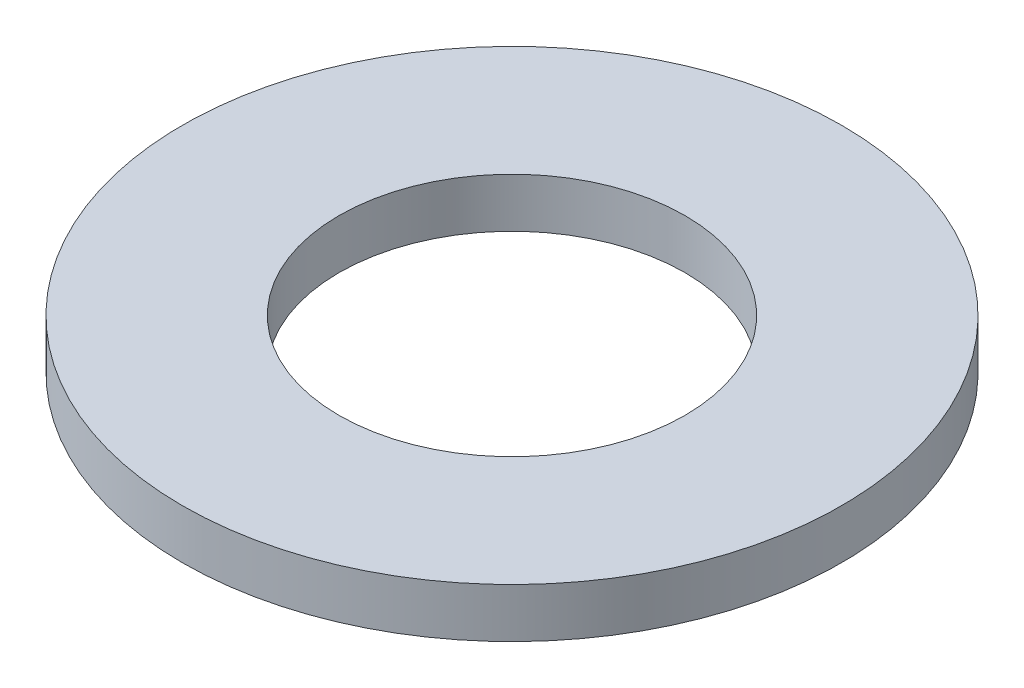
SolidWorks part; units mm, degrees
ref_plane "前视基准面" through (0, 0, 0) normal (0, 0, 1) x (1, 0, 0)
ref_plane "上视基准面" through (0, 0, 0) normal (0, 1, 0) x (1, 0, 0)
ref_plane "右视基准面" through (0, 0, 0) normal (1, 0, 0) x (0, 0, -1)
sketch "草图1" plane through (0, 0, 0) normal (0, 1, 0) x (1, 0, 0)
  circle A0 centre (0, 0) radius 2.1
  circle A1 centre (0, 0) radius 4
  dimension "D1" = 4.2
  dimension "D2" = 8
extrude "凸台-拉伸1" add sketch "草图1" along normal blind 0.6
